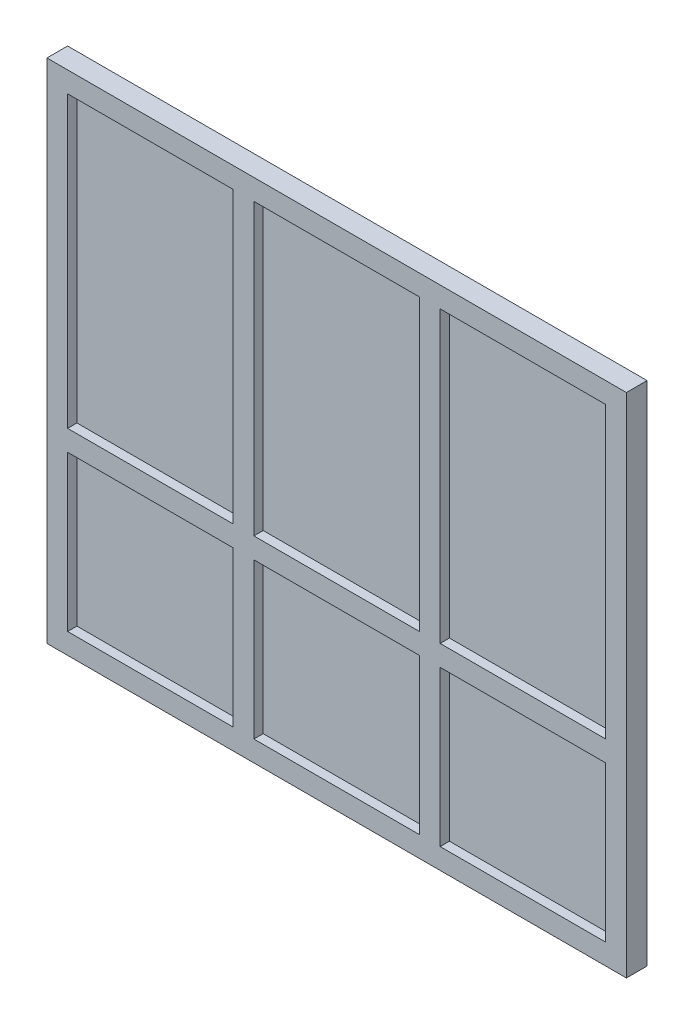
SolidWorks part; units mm, degrees
ref_plane "Спереди" through (0, 0, 0) normal (0, 0, 1) x (1, 0, 0)
ref_plane "Сверху" through (0, 0, 0) normal (0, 1, 0) x (1, 0, 0)
ref_plane "Справа" through (0, 0, 0) normal (1, 0, 0) x (0, 0, -1)
other "Configuration Table"
sketch "Эскиз1" plane through (0, 0, 0) normal (0, 0, 1) x (1, 0, 0)
  line L0 (-1300, 2350) -> (-1300, 950)
  line L1 (1400, 0) -> (-1400, 0)
  line L2 (1400, 0) -> (1400, 2450)
  line L3 (1400, 2450) -> (-1400, 2450)
  line L4 (-1400, 0) -> (-1400, 2450)
  line L5 (-1300, 950) -> (-500, 950)
  line L6 (-500, 950) -> (-500, 2350)
  line L7 (-1300, 2350) -> (-500, 2350)
  line L9 (-1300, 100) -> (-500, 100)
  line L11 (-400, 2350) -> (400, 2350)
  line L13 (-400, 100) -> (400, 100)
  line L15 (500, 2350) -> (1300, 2350)
  line L17 (500, 100) -> (1300, 100)
  line L19 (-1300, 100) -> (-1300, 850)
  line L20 (-1300, 850) -> (-500, 850)
  line L21 (-500, 850) -> (-500, 100)
  line L22 (-400, 100) -> (-400, 850)
  line L23 (-400, 850) -> (400, 850)
  line L24 (400, 850) -> (400, 100)
  line L25 (500, 100) -> (500, 850)
  line L26 (500, 850) -> (1300, 850)
  line L27 (1300, 850) -> (1300, 100)
  line L28 (-400, 2350) -> (-400, 950)
  line L29 (-400, 950) -> (400, 950)
  line L30 (400, 950) -> (400, 2350)
  line L31 (500, 2350) -> (500, 950)
  line L32 (500, 950) -> (1300, 950)
  line L33 (1300, 950) -> (1300, 2350)
  line L34 (-500, 2350) -> (-400, 2350) construction
  line L35 (400, 2350) -> (500, 2350) construction
  line L36 (-500, 850) -> (-400, 850) construction
  line L37 (1300, 2350) -> (1400, 2350) construction
  line L38 (400, 850) -> (500, 850) construction
  line L39 (1300, 850) -> (1300, 950) construction
  line L40 (500, 850) -> (500, 950) construction
  line L41 (400, 850) -> (400, 950) construction
  line L42 (400, 950) -> (500, 950) construction
  line L43 (-500, 950) -> (-400, 950) construction
  line L44 (-400, 950) -> (-400, 850) construction
  line L45 (-500, 850) -> (-500, 950) construction
  line L46 (-1300, 850) -> (-1300, 950) construction
  line L47 (-500, 100) -> (-400, 100) construction
  line L48 (400, 100) -> (500, 100) construction
  line L49 (-1300, 2350) -> (-1400, 2350) construction
  line L50 (-1400, 2350) -> (-1300, 2350) construction
  line L51 (-1300, 2350) -> (-1300, 2450) construction
  line L52 (-1300, 100) -> (-1300, 0) construction
  point P0 (0, 0)
  point P5 (0, 0)
  point P24 (0, 0)
  point P35 (0, 88.0963)
  point P36 (0, 0)
  point P37 (0, 0)
  point P38 (0, 0)
  point P39 (-1300, 1075.5064)
  dimension "D1" = 2800
  dimension "D2" = 2450
  dimension "D3" = 1400
  dimension "D4" = 100
extrude "Бобышка-Вытянуть1" add sketch "Эскиз1" along normal blind 100
ref_plane "Плоскость1" through (0, 0, 50) normal (0, 0, -1) x (-1, 0, 0)
sketch "Эскиз2" plane through (0, 0, 50) normal (0, 0, -1) x (-1, 0, 0)
  line L1 (-1300, 2350) -> (1300, 2350)
  line L2 (-1300, 2350) -> (-1300, 100)
  line L3 (-1300, 100) -> (1300, 100)
  line L4 (1300, 2350) -> (1300, 100)
extrude "Бобышка-Вытянуть2" add sketch "Эскиз2" along normal mid plane 10 separate body
